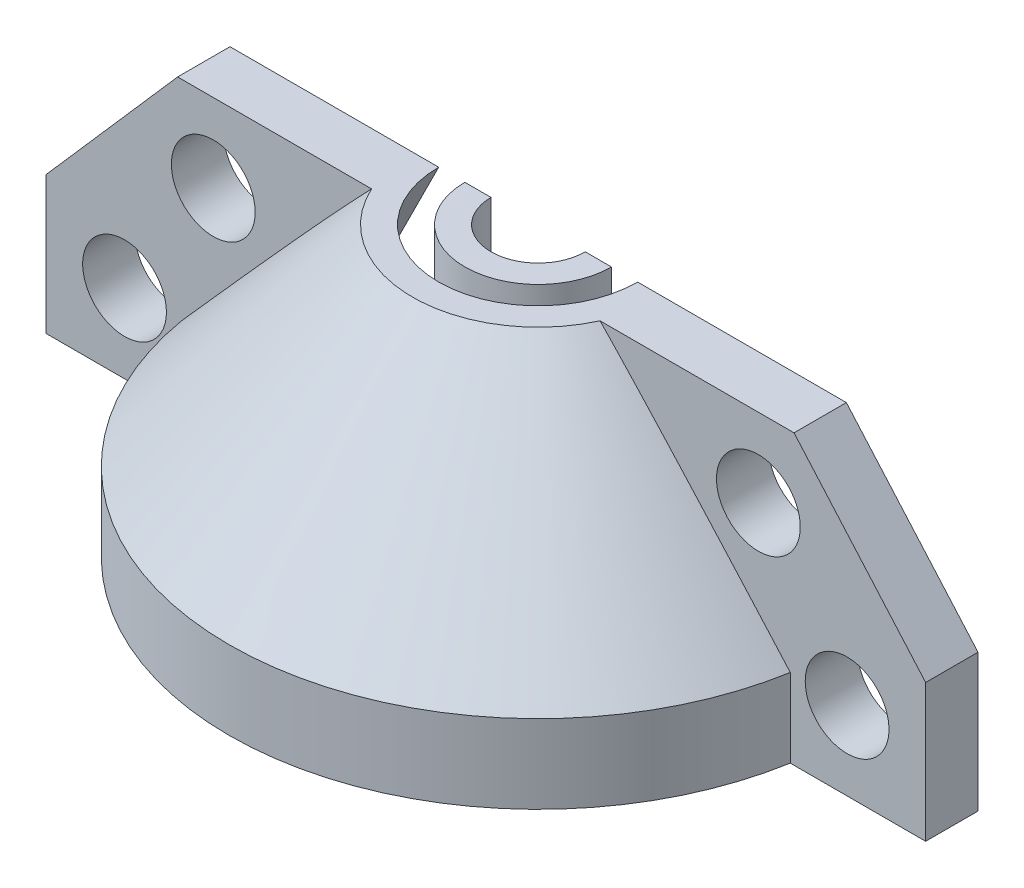
SolidWorks part; units mm, degrees
ref_plane "Front Plane" through (0, 0, 0) normal (0, 0, 1) x (1, 0, 0)
ref_plane "Top Plane" through (0, 0, 0) normal (0, 1, 0) x (1, 0, 0)
ref_plane "Right Plane" through (0, 0, 0) normal (1, 0, 0) x (0, 0, -1)
sketch "Sketch1" plane through (0, 0, 0) normal (0, 0, 1) x (1, 0, 0)
  line L0 (0, 0) -> (0, 12.4672) construction
  line L1 (-1.8, 0) -> (-1.8, 8)
  line L2 (-1.8, 0) -> (-2.8, 0)
  line L3 (-1.8, 8) -> (-2.8, 8)
  line L4 (-2.8, 0) -> (-2.8, 8)
  line L5 (-3.8, 8) -> (-7.8, 0)
  line L6 (-7.8, 0) -> (-10.8, 0)
  line L7 (-10.8, 0) -> (-3.8, 8)
  line L9 (-10.8, 0) -> (-1.8, 0)
  line L10 (-10.8, 0) -> (-10.8, -3)
  line L11 (-1.8, 0) -> (-1.8, -3)
  line L12 (-10.8, -3) -> (-1.8, -3)
  line L13 (-3.8, 8) -> (-2.8, 8) construction
  dimension "D1" = 1.8
  dimension "D2" = 1
  dimension "D3" = 3
  dimension "D4" = 1
  dimension "D5" = 8
  dimension "D6" = 5
  dimension "D7" = 3
revolve "Revolve1" add sketch "Sketch1" angle 180 about L0
sketch "Sketch2" plane through (0, 0, 0) normal (0, 0, -1) x (-1, 0, 0)
  line L0 (-10.8, -3) -> (-16.8, -3)
  line L1 (-10.8, -3) -> (-10.8, 0)
  line L2 (-16.8, -3) -> (-16.8, 2.2544)
  line L4 (-3.8, 8) -> (-11.7726, 8)
  line L5 (-11.7726, 8) -> (-16.8, 2.2544)
  line L6 (-10.8, 0) -> (-3.8, 8) construction
  line L7 (-10.8, 0) -> (-3.8, 8)
  line L8 (-10.4113, 5) -> (-8.1536, 3.0245) construction
  line L9 (-10.4113, 5) -> (-12.669, 6.9755) construction
  line L10 (0, 0) -> (0, 11.7241) construction
  line L11 (10.4113, 5) -> (12.669, 6.9755) construction
  line L12 (10.4113, 5) -> (8.1536, 3.0245) construction
  line L13 (10.8, 0) -> (3.8, 8)
  line L14 (11.7726, 8) -> (16.8, 2.2544)
  line L15 (3.8, 8) -> (11.7726, 8)
  line L16 (16.8, -3) -> (16.8, 2.2544)
  line L17 (10.8, -3) -> (10.8, 0)
  line L18 (10.8, -3) -> (16.8, -3)
  circle A0 centre (-10.4113, 5) radius 1.6
  circle A2 centre (-13.8, 0) radius 1.6
  circle A3 centre (13.8, 0) radius 1.6
  circle A4 centre (10.4113, 5) radius 1.6
  dimension "D1" = 3.2
  dimension "D2" = 3
  dimension "D3" = 3
  dimension "D4" = 6
  dimension "D5" = 3
  dimension "D6" = 3
  dimension "D7" = 3
extrude "Boss-Extrude1" add sketch "Sketch2" against normal blind 2 separate body
sketch "Sketch3" plane through (0, 0, 0) normal (0, 0, -1) x (-1, 0, 0)
  line L0 (-11.8, -3) -> (-11.8, 0)
  line L1 (-16.8, -3) -> (-10.8, -3) construction
  line L2 (-11.8, 0) -> (-4.8, 8)
  line L3 (-3.8, 8) -> (-11.7726, 8) construction
  line L4 (0, 0) -> (0, 11.82) construction
  line L10 (-10.8, 0) -> (-3.8, 8)
  line L11 (-3.8, 8) -> (-11.7726, 8)
  line L12 (-11.7726, 8) -> (-16.8, 2.2544)
  line L13 (-16.8, 2.2544) -> (-16.8, -3)
  line L14 (-16.8, -3) -> (-10.8, -3)
  line L15 (-10.8, -3) -> (-10.8, 0)
  line L16 (-10.8, 0) -> (-3.8, 8)
  line L17 (-3.8, 8) -> (-4.8, 8)
  line L20 (-11.8, -3) -> (-10.8, -3)
  line L21 (-10.8, -3) -> (-10.8, 0)
  dimension "D2" = 1
  dimension "D3" = 1
  dimension "D1" = 0
revolve "Revolve2" add sketch "Sketch3" angle 180 about L4
